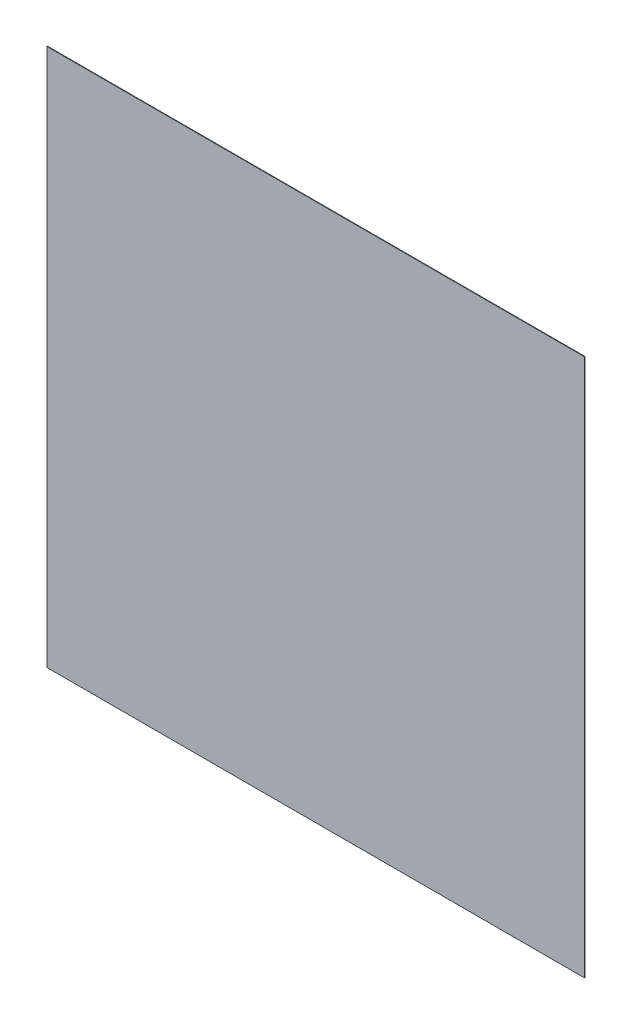
SolidWorks part; units mm, degrees
ref_plane "前视基准面" through (0, 0, 0) normal (0, 0, 1) x (1, 0, 0)
ref_plane "上视基准面" through (0, 0, 0) normal (0, 1, 0) x (1, 0, 0)
ref_plane "右视基准面" through (0, 0, 0) normal (1, 0, 0) x (0, 0, -1)
sketch "草图1" plane through (0, 0, 0) normal (0, 0, 1) x (1, 0, 0)
  line L1 (0, 0) -> (10000, 0)
  line L2 (0, 0) -> (0, 10000)
  line L3 (0, 10000) -> (10000, 10000)
  line L4 (10000, 0) -> (10000, 10000)
extrude "凸台-拉伸1" add sketch "草图1" along normal blind 10
